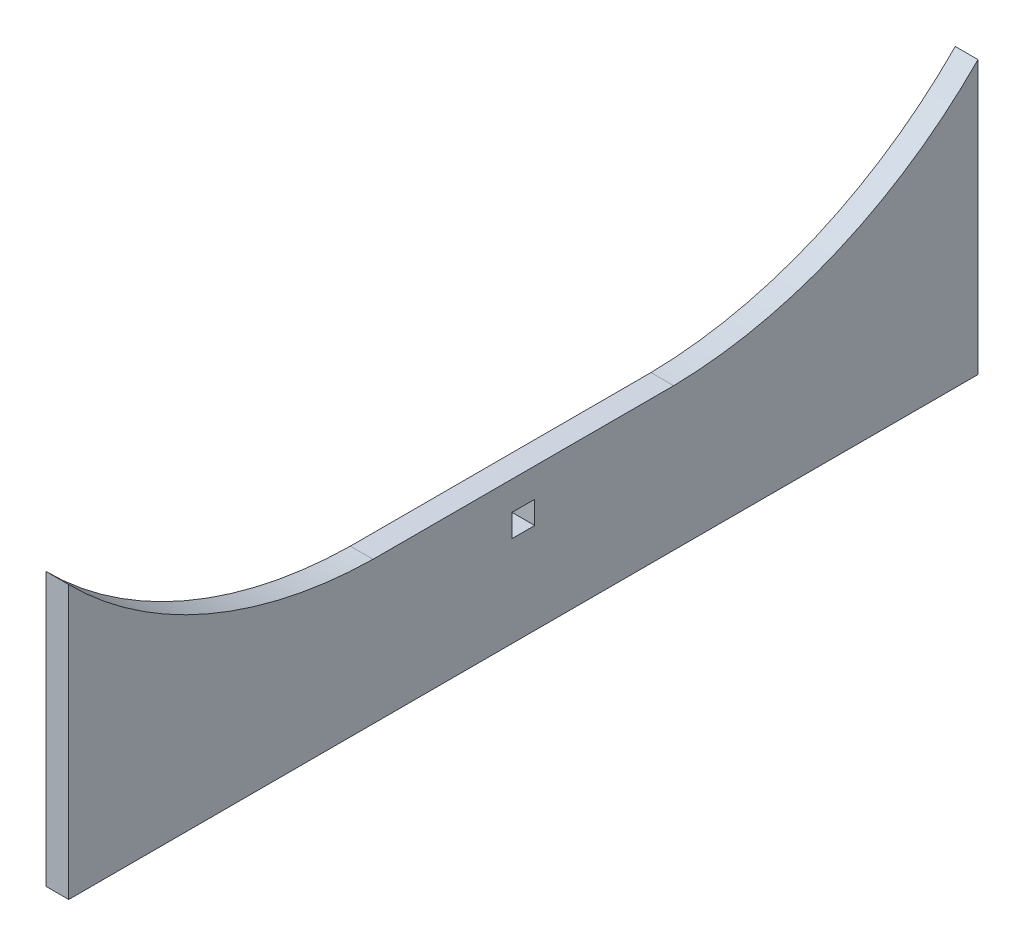
SolidWorks part; units mm, degrees
ref_plane "Front" through (0, 0, 0) normal (0, 0, 1) x (1, 0, 0)
ref_plane "Top" through (0, 0, 0) normal (0, 1, 0) x (1, 0, 0)
ref_plane "Right" through (0, 0, 0) normal (1, 0, 0) x (0, 0, -1)
sketch "Sketch1" plane through (0, 0, 0) normal (1, 0, 0) x (0, 0, -1)
  line L0 (-42, 1.7114) -> (42, 1.7114)
  line L2 (-127, 38.1) -> (-127, -38.1)
  line L3 (-127, -38.1) -> (127, -38.1)
  line L4 (127, 38.1) -> (127, -38.1)
  line L5 (-127, 38.1) -> (127, -38.1) construction
  line L6 (-127, -38.1) -> (127, 38.1) construction
  line L7 (-3.175, -6.35) -> (3.175, -6.35)
  line L8 (-3.175, -6.35) -> (-3.175, -12.7)
  line L9 (-3.175, -12.7) -> (3.175, -12.7)
  line L10 (3.175, -6.35) -> (3.175, -12.7)
  line L11 (-3.175, -6.35) -> (3.175, -12.7) construction
  line L12 (-3.175, -12.7) -> (3.175, -6.35) construction
  arc A0 (-127, 38.1) -> (-42, 1.7114) centre (-39.9782, 123.904) ccw
  arc A1 (127, 38.1) -> (42, 1.7114) centre (39.9782, 123.904) cw
  point P0 (0, 0)
  point P6 (0, -9.525)
  dimension "D1" = 76.2
  dimension "D2" = 254
  dimension "D3" = 85
  dimension "D4" = 6.35
  dimension "D5" = 6.35
  dimension "D6" = 123.825
  dimension "D7" = 85
extrude "Boss-Extrude1" add sketch "Sketch1" along normal blind 6.35
